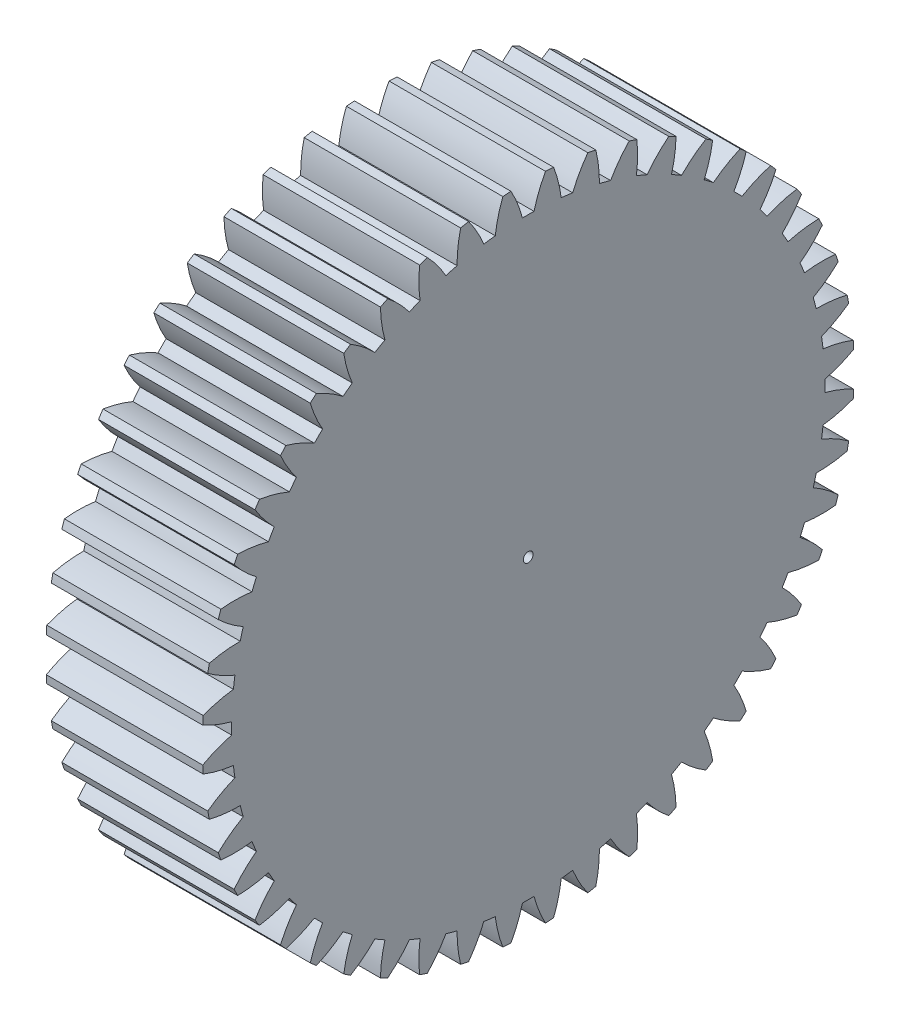
SolidWorks part; units mm, degrees
ref_plane "Plane1" through (0, 0, 0) normal (0, 0, 1) x (1, 0, 0)
ref_plane "Plane2" through (0, 0, 0) normal (0, 1, 0) x (1, 0, 0)
ref_plane "Plane3" through (0, 0, 0) normal (1, 0, 0) x (0, 0, -1)
other "Configuration Table"
sketch "HoldingSke" plane through (0, 0, 0) normal (0, 1, 0) x (1, 0, 0)
  line L0 (0, 0) -> (407.902, -453.0211)
  line L1 (-15, 0) -> (100, 0) construction
  line L2 (0, 0) -> (-2.1039, 2.3779)
  line L3 (0, 0) -> (-11.863, 4.5341)
  line L4 (0, 0) -> (5.7786, 6.4178)
  line L5 (0, 0) -> (-47.5972, -17.7524)
  line L6 (0, 0) -> (-10.5278, -7.1032)
  line L7 (-2.1039, 2.3779) -> (8.8308, 51.9871)
  line L8 (-76.2, 54.61) -> (-75.184, 54.61)
  line L9 (-71.009, 38.7566) -> (-53.1078, 45.2721)
  line L10 (-76.2, 71.12) -> (104.1128, 71.12)
  line L11 (0, 0) -> (-12.7, 0)
  line L12 (-76.2, 101.6) -> (-76.1573, 101.6)
  line L13 (24.9733, 27.94) -> (52.9518, 28.4284)
  line L14 (24.9733, 27.94) -> (25.0241, 27.9398)
  line L15 (24.9733, 27.94) -> (100.4021, 29.52)
  circle A0 centre (0, 0) radius 0.3969
  circle A1 centre (0, 0) radius 24.0792
  circle A2 centre (0, 0) radius 38.1
  circle A3 centre (0, 0) radius 0.3969
  dimension "MHD" = 48.1584
  dimension "Hub_dia" = 76.2
  dimension "Bore" = 0.7937
  dimension "MBD" = 0.7937
  dimension "Num_teeth" = 48
  dimension "Pitch" = 609.6
  dimension "Overall_len" = 50.8
  dimension "Show_teeth" = 48
  dimension "Thickness" = 12.7
  dimension "OAL" = 50.8001
  dimension "T_dim" = 1.016
  dimension "Ap" = 20
  dimension "H" = 19.05
  dimension "Pitch_radius" = 180.3128
  dimension "Width" = 12.7
  dimension "Backlash" = 0.0427
  dimension "Addendum_fac" = 1
  dimension "Dedendum_fac" = 1.2
  dimension "Clearance_fac" = 0.2
  dimension "Dedendum_add" = 0.0508
sketch "BasProSke" plane through (0, 0, 0) normal (0, 1, 0) x (1, 0, 0)
  line L0 (-10, 0) -> (60, 0) construction
  line L1 (0, 0) -> (0, 26.4583)
  line L2 (0, 0) -> (12.7, 0)
  line L3 (12.7, 0) -> (12.7, 26.4583)
  line L4 (12.7, 26.4583) -> (0, 26.4583)
  dimension "Thickness" = 12.7
  dimension "Diameter" = 52.9167
revolve "Base-Revolve" add sketch "BasProSke" angle 360 about L0
sketch "TooCutSke" plane through (0, 0, 0) normal (1, 0, 0) x (0, 0, -1)
  line L1 (0, 0) -> (0, 107) construction
  line L2 (0, 0) -> (-0.9057, 25.3838) construction
  line L3 (0, 0) -> (-3.321, 50.6688) construction
  line L4 (-0.9057, 25.3838) -> (-1.6605, 25.3344) construction
  arc A0 (0.47, 24.0746) -> (-0.47, 24.0746) centre (0, 0) ccw
  arc A1 (1.4151, 26.4459) -> (-1.4151, 26.4459) centre (0, 0) ccw
  circle A2 centre (0, 0) radius 25.4 construction
  circle A3 centre (0, 0) radius 23.8682 construction
  arc A4 (-0.47, 24.0746) -> (-1.4151, 26.4459) centre (-10.3059, 21.5286) ccw
  arc A5 (1.4151, 26.4459) -> (0.47, 24.0746) centre (10.3059, 21.5286) ccw
  dimension "Root_dia" = 48.1584
  dimension "Overcut_dia" = 52.9675
  dimension "Pitch_dia" = 50.8
  dimension "Base_dia" = 47.7364
  dimension "Flank_rad" = 10.16
  dimension "Half_ang" = 3.75
  dimension "Half_CT" = 0.7564
extrude "ToothCut" cut sketch "TooCutSke" along normal through all
fillet "Breaks" [suppressed] radius 0.0212
fillet "RootFillets" [suppressed] radius 0.2625
pattern_circular "TeethCuts" count 48 every 7.5 about axis through (-10, 0, 0) along (1, 0, 0) of "ToothCut", "RootFillets", "Breaks"
sketch "HubNeaOneSke" plane through (0, 0, 0) normal (-1, 0, 0) x (0, 0, 1)
  circle A0 centre (0, 0) radius 24.0792
  dimension "Diameter" = 48.1584
extrude "HubNearOne" [suppressed] add sketch "HubNeaOneSke" along normal blind 38.1001
sketch "HubNeaBotSke" plane through (0, 0, 0) normal (-1, 0, 0) x (0, 0, 1)
  circle A0 centre (0, 0) radius 24.0792
  dimension "Diameter" = 48.1584
extrude "HubNearBoth" [suppressed] add sketch "HubNeaBotSke" along normal blind 19.05
ref_plane "FarPln" through (12.7, 0, 0) normal (1, 0, 0) x (0, 0, -1)
sketch "HubFarSke" plane through (12.7, 0, 0) normal (1, 0, 0) x (0, 0, -1)
  circle A0 centre (0, 0) radius 24.0792
  dimension "Diameter" = 48.1584
extrude "HubFar" [suppressed] add sketch "HubFarSke" along normal blind 19.05
sketch "BorSke" plane through (0, 0, 0) normal (1, 0, 0) x (0, 0, -1)
  circle A0 centre (0, 0) radius 0.3969
  dimension "Diameter" = 0.7937
extrude "Bore" cut sketch "BorSke" along normal mid plane 101.6001
sketch "KeySke" plane through (0, 0, 0) normal (1, 0, 0) x (0, 0, -1)
  line L0 (-0.127, 0) -> (-0.127, 0.6191)
  line L1 (-0.127, 0.6191) -> (0.127, 0.6191)
  line L2 (0.127, 0.6191) -> (0.127, 0)
  line L3 (0, 0) -> (0, 34) construction
  line L4 (-0.127, 0) -> (0.127, 0)
  dimension "Offset" = 0.6191
  dimension "Width" = 0.254
extrude "Keyway" [suppressed] cut sketch "KeySke" along normal mid plane 101.6001
pattern_circular "Keyway2" [suppressed] count 2 every 90 about axis through (-10, 0, 0) along (1, 0, 0)
equation "' \"Pitch@HoldingSke\" = 4"
equation "' \"Num_teeth@HoldingSke\" = 12"
equation "' \"Ap@HoldingSke\" =  20"
equation "' \"Ap@HoldingSke\" = 20"
equation "' \"Width@HoldingSke\" = 0.5"
equation "' \"Hub_dia@HoldingSke\"= 1"
equation "' \"Hub_dia@HoldingSke\" = 1"
equation "' \"Overall_len@HoldingSke\" = 1.0"
equation "' \"Bore@HoldingSke\" = 0.75"
equation "' \"T_dim@HoldingSke\" = 0.85"
equation "' \"Width@KeySke\" = 0.25"
equation "' \"Show_teeth@HoldingSke\" = 13"
equation "' \"Backlash@HoldingSke\" = 0.009"
equation "' \"Addendum_fac@HoldingSke\" = 1.0"
equation "' \"Dedendum_fac@HoldingSke\" = 1.25"
equation "' \"Dedendum_add@HoldingSke\" = 0.00005"
equation "' \"Clearance_fac@HoldingSke\" = 0.25"
equation "' \"Pitch@HoldingSke\" = 0.5"
equation "' \"Num_teeth@HoldingSke\" = 23"
equation "' \"Show_teeth@HoldingSke\" = 23"
equation "' \"Backlash@HoldingSke\" = 0.0375"
equation "\"Overcut_dia@TooCutSke\" = (\"Num_teeth@HoldingSke\" + 2 * \"Addendum_fac@HoldingSke\") / \"Pitch@HoldingSke\" + 0.002"
equation "\"Pitch_dia@TooCutSke\" = \"Num_teeth@HoldingSke\" / \"Pitch@HoldingSke\""
equation "\"Base_dia@TooCutSke\" = \"Num_teeth@HoldingSke\" / \"Pitch@HoldingSke\" * cos((\"Ap@HoldingSke\"  * 3.14159265 / 180))"
equation "\"Root_dia@TooCutSke\" = (\"Num_teeth@HoldingSke\" + 2) / \"Pitch@HoldingSke\" - 2 * (\"Addendum_fac@HoldingSke\" + \"Dedendum_fac@HoldingSke\") / \"Pitch@HoldingSke\" - \"Dedendum_add@HoldingSke\" * 2"
equation "\"Half_ang@TooCutSke\" = 180 / \"Num_teeth@HoldingSke\""
equation "\"Half_CT@TooCutSke\" = \"Num_teeth@HoldingSke\" / \"Pitch@HoldingSke\" * sin((3.14159265 / 2 / \"Num_teeth@HoldingSke\")) / 2 - 7 * \"Backlash@HoldingSke\" / 4"
equation "\"Flank_rad@TooCutSke\" = \"Num_teeth@HoldingSke\" / \"Pitch@HoldingSke\" / 5"
equation "\"Radius@RootFillets\" = \"Clearance_fac@HoldingSke\" / \"Pitch@HoldingSke\" + \"Dedendum_add@HoldingSke\""
equation "\"Break_rad@Breaks\" = 0.02 / \"Pitch@HoldingSke\""
equation "\"Thickness@HoldingSke\" = \"Width@HoldingSke\""
equation "\"OAL@HoldingSke\" = \"Thickness@HoldingSke\""
equation "\"MHD@HoldingSke\" = (\"Num_teeth@HoldingSke\" + 2) / \"Pitch@HoldingSke\" - 2 * (\"Addendum_fac@HoldingSke\" + \"Dedendum_fac@HoldingSke\")  / \"Pitch@HoldingSke\" - \"Dedendum_add@HoldingSke\" * 2"
equation "\"MBD@HoldingSke\" = (\"Num_teeth@HoldingSke\" + 2) / \"Pitch@HoldingSke\" - 2 * (\"Addendum_fac@HoldingSke\" + \"Dedendum_fac@HoldingSke\")  / \"Pitch@HoldingSke\" - \"Dedendum_add@HoldingSke\" * 2 - 0.002"
equation "\"MHD@HoldingSke\" = ((sgn( \"MHD@HoldingSke\" - \"Hub_dia@HoldingSke\" )-1)*( \"MHD@HoldingSke\" - \"Hub_dia@HoldingSke\" ))/-2+ \"Hub_dia@HoldingSke\""
equation "\"MBD@HoldingSke\" = ((sgn( \"MBD@HoldingSke\" - \"Bore@HoldingSke\" )-1)*( \"MBD@HoldingSke\" - \"Bore@HoldingSke\" ))/-2+ \"Bore@HoldingSke\""
equation "\"OAL@HoldingSke\" = ((sgn( \"OAL@HoldingSke\" - \"Overall_len@HoldingSke\" )+1)*( \"OAL@HoldingSke\" - \"Overall_len@HoldingSke\" ))/2 + \"Overall_len@HoldingSke\" + 0.000002"
equation "\"Num_teeth@TeethCuts\" = int( \"Show_teeth@HoldingSke\" ) + 1"
equation "\"Num_teeth@TeethCuts\" = ((sgn( \"Num_teeth@TeethCuts\" - \"Num_teeth@HoldingSke\" )-1)*( \"Num_teeth@TeethCuts\" - \"Num_teeth@HoldingSke\" ))/-2+ \"Num_teeth@HoldingSke\""
equation "\"Num_teeth@TeethCuts\" = ((sgn( \"Num_teeth@TeethCuts\" - 2.0)+1)*( \"Num_teeth@TeethCuts\" - 2.0))/2 +2.0"
equation "\"Angle@TeethCuts\" = 360.0 / \"Num_teeth@HoldingSke\""
equation "\"Diameter@BasProSke\" = (\"Num_teeth@HoldingSke\" + 2 * \"Addendum_fac@HoldingSke\") / \"Pitch@HoldingSke\""
equation "\"Thickness@BasProSke\"  = \"Thickness@HoldingSke\""
equation "' \"Fillet_rad@BasProSke\" =  \"Thickness@HoldingSke\" * 0.05"
equation "' \"Fillet_rad@BasProSke\" = \"Thickness@HoldingSke\" * 0.05"
equation "\"MHD@HoldingSke\" = ((sgn( \"MHD@HoldingSke\" - \"Root_dia@TooCutSke\" )-1)*( \"MHD@HoldingSke\" - \"Root_dia@TooCutSke\" ))/-2+ \"Root_dia@TooCutSke\""
equation "\"Diameter@HubNeaOneSke\" = \"MHD@HoldingSke\""
equation "\"Length@HubNearOne\" = \"OAL@HoldingSke\" - \"Thickness@BasProSke\""
equation "\"Diameter@HubNeaBotSke\" = \"MHD@HoldingSke\""
equation "\"Length@HubNearBoth\" = ( \"OAL@HoldingSke\" - \"Thickness@BasProSke\" ) / 2.0"
equation "\"Thickness@FarPln\" = \"Thickness@BasProSke\""
equation "\"Diameter@HubFarSke\" = \"MHD@HoldingSke\""
equation "\"Length@HubFar\" = ( \"OAL@HoldingSke\" - \"Thickness@BasProSke\" ) / 2.0"
equation "\"Diameter@BorSke\" = \"MBD@HoldingSke\""
equation "\"D1@Bore\" = \"OAL@HoldingSke\" * 2.0"
equation "\"D1@Keyway\" = \"OAL@HoldingSke\" * 2.0"
equation "\"Offset@KeySke\" = \"T_dim@HoldingSke\" - \"MBD@HoldingSke\" / 2.0"
